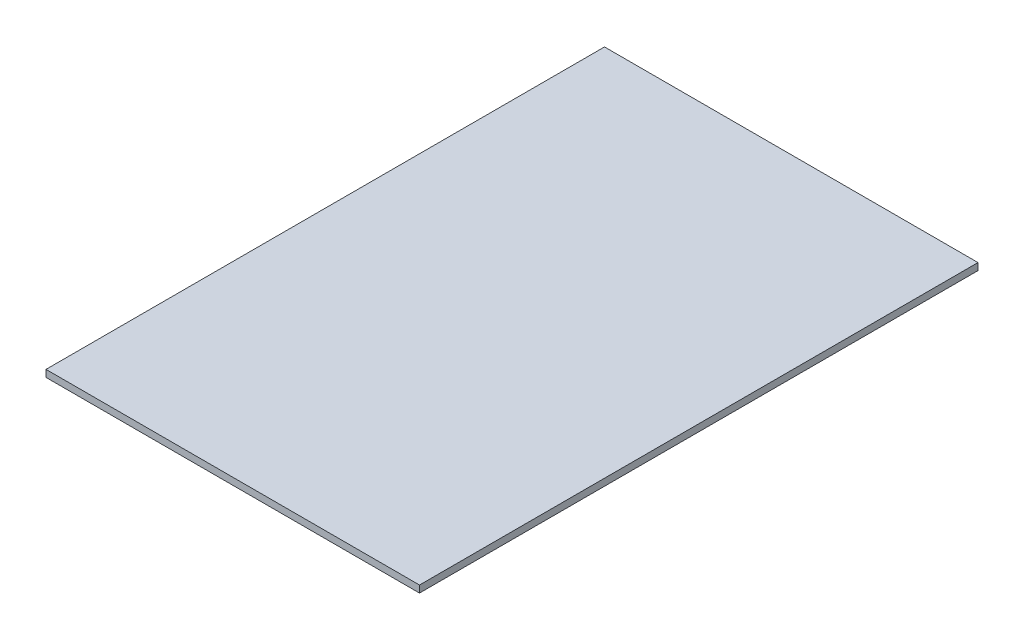
SolidWorks part; units mm, degrees
ref_plane "Front Plane" through (0, 0, 0) normal (0, 0, 1) x (1, 0, 0)
ref_plane "Top Plane" through (0, 0, 0) normal (0, 1, 0) x (1, 0, 0)
ref_plane "Right Plane" through (0, 0, 0) normal (1, 0, 0) x (0, 0, -1)
sketch "Sketch2" plane through (0, 0, 0) normal (0, 1, 0) x (1, 0, 0)
  line L1 (0, 0) -> (-107, 0)
  line L2 (0, 0) -> (0, -160)
  line L3 (0, -160) -> (-107, -160)
  line L4 (-107, 0) -> (-107, -160)
  dimension "D1" = 160
  dimension "D2" = 107
extrude "Boss-Extrude1" add sketch "Sketch2" along normal blind 2
